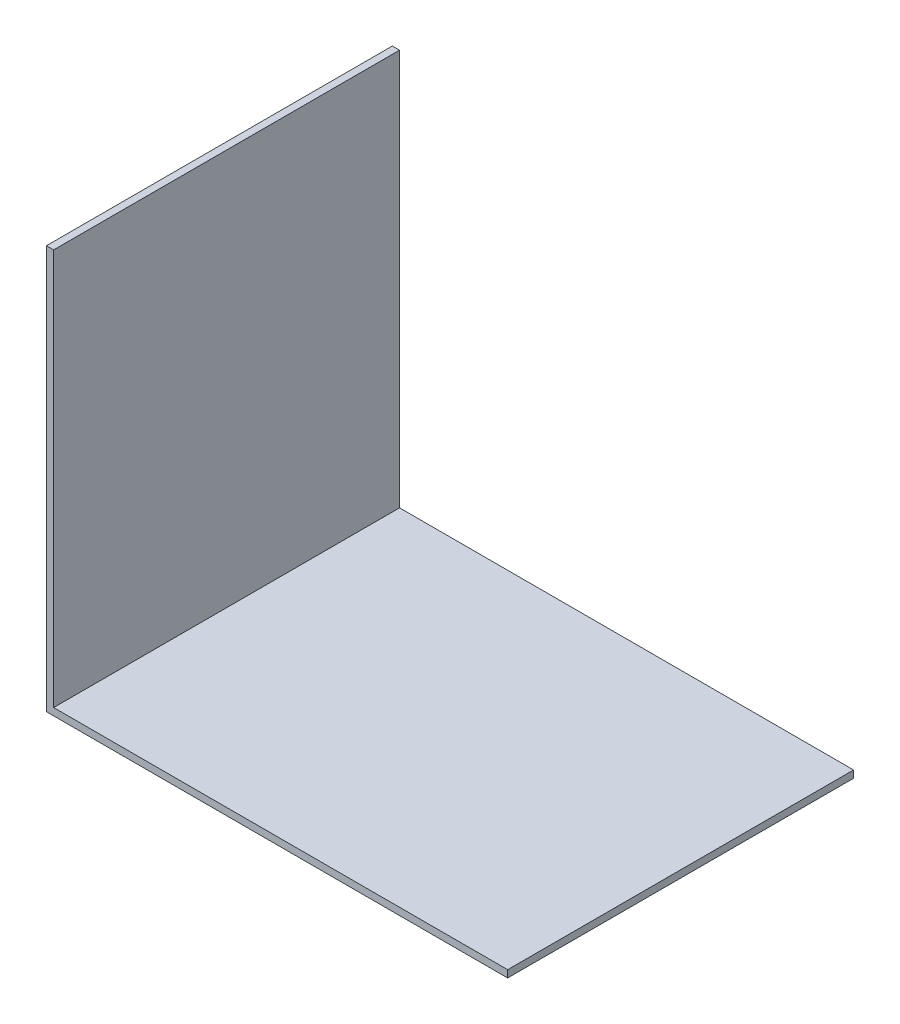
SolidWorks part; units mm, degrees
material "Glass"
ref_plane "Front Plane" through (0, 0, 0) normal (0, 0, 1) x (1, 0, 0)
ref_plane "Top Plane" through (0, 0, 0) normal (0, 1, 0) x (1, 0, 0)
ref_plane "Right Plane" through (0, 0, 0) normal (1, 0, 0) x (0, 0, -1)
sketch "Sketch2" plane through (0, 0, 0) normal (0, 0, 1) x (1, 0, 0)
  line L1 (21.1133, 21.7856) -> (224.3133, 21.7856)
  line L2 (21.1133, 21.7856) -> (21.1133, 199.5856)
  line L3 (21.1133, 199.5856) -> (224.3133, 199.5856)
  line L4 (224.3133, 21.7856) -> (224.3133, 199.5856)
  line L5 (224.3133, 199.5856) -> (24.2883, 199.5856)
  line L6 (224.3133, 199.5856) -> (224.3133, 24.9606)
  line L7 (224.3133, 24.9606) -> (24.2883, 24.9606)
  line L8 (24.2883, 199.5856) -> (24.2883, 24.9606)
  dimension "D1" = 3.175
  dimension "D2" = 3.175
  dimension "D3" = 203.2
  dimension "D4" = 177.8
extrude "Boss-Extrude1" add sketch "Sketch2" along normal blind 152.4 contours L8 L3 L2 L1 L4 L7
